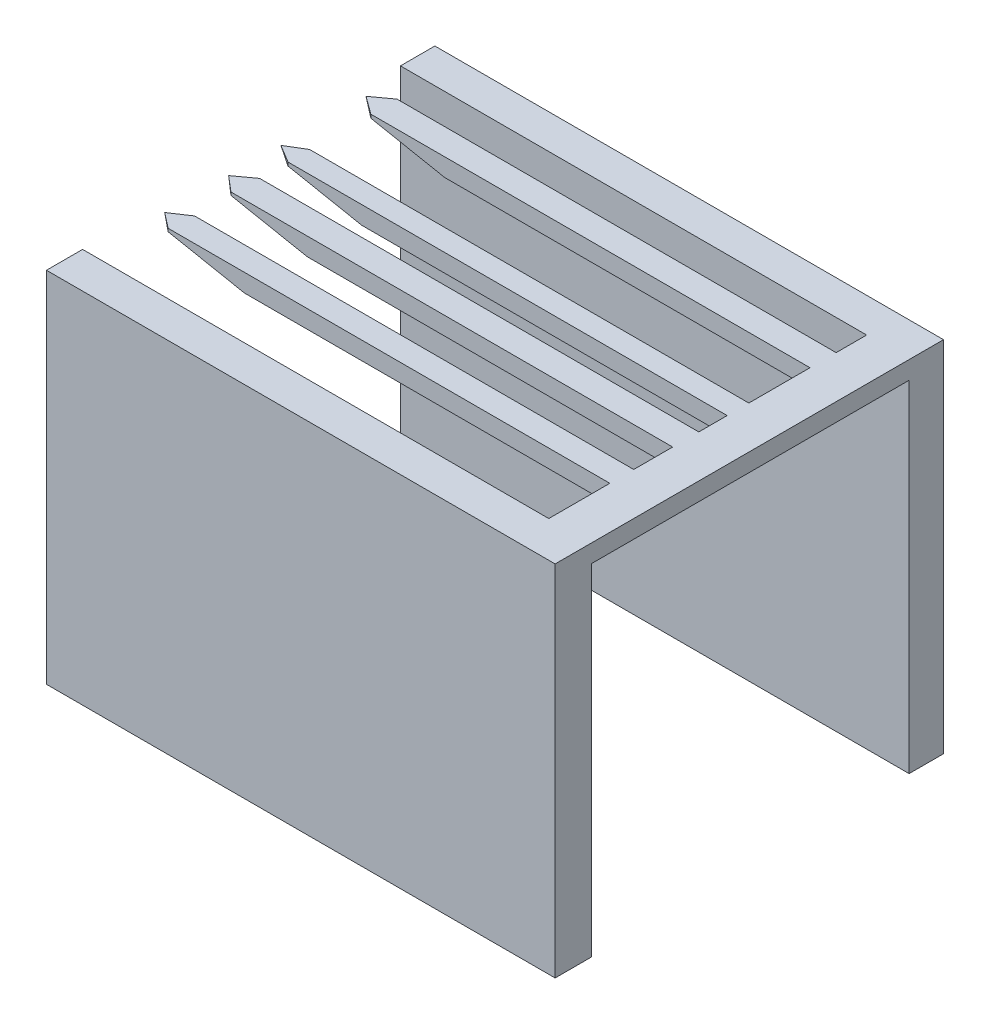
SolidWorks part; units mm, degrees
ref_plane "Front Plane" through (0, 0, 0) normal (0, 0, 1) x (1, 0, 0)
ref_plane "Top Plane" through (0, 0, 0) normal (0, 1, 0) x (1, 0, 0)
ref_plane "Right Plane" through (0, 0, 0) normal (1, 0, 0) x (0, 0, -1)
sketch "Sketch1" plane through (0, 0, 22.0657) normal (0, 1, 0) x (1, 0, 0)
  line L1 (-54.1532, 26.5268) -> (87.6897, 26.5268)
  line L2 (-54.1532, 26.5268) -> (-54.1532, -81.7796)
  line L3 (-54.1532, -81.7796) -> (87.6897, -81.7796)
  line L4 (87.6897, 26.5268) -> (87.6897, -81.7796)
  point P4 (87.6897, -81.7796)
extrude "Boss-Extrude1" add sketch "Sketch1" along normal blind 5
sketch "Sketch2" plane through (0, 5, 22.0657) normal (0, 1, 0) x (1, 0, 0)
  line L0 (87.6897, -81.7796) -> (87.6897, 26.5268) construction
  line L1 (-54.1532, -81.7796) -> (87.6897, -81.7796)
  line L2 (-54.1532, -81.7796) -> (-54.1532, -44.8027)
  line L3 (-54.1532, -44.8027) -> (57.7742, -44.8027)
  line L4 (87.6897, -81.7796) -> (87.6897, -44.8027)
  line L5 (57.7742, -44.8027) -> (57.7742, 16.927)
  line L6 (87.6897, 26.5268) -> (-54.1532, 26.5268) construction
  line L7 (57.7742, 26.5268) -> (87.6897, 26.5268)
  line L8 (87.6897, 26.5268) -> (87.6897, -44.8027)
  line L9 (-54.1532, 26.5268) -> (57.7742, 26.5268)
  line L10 (57.7742, 16.927) -> (-54.1532, 16.927)
  line L11 (-54.1532, 26.5268) -> (-54.1532, -81.7796) construction
  line L12 (-54.1532, 16.927) -> (-54.1532, 26.5268)
extrude "Boss-Extrude2" add sketch "Sketch2" along normal blind 95
sketch "Sketch3" plane through (0, 5, 22.0657) normal (0, 1, 0) x (1, 0, 0)
  line L4 (-54.1532, -44.8027) -> (57.7742, -44.8027)
  line L5 (57.7742, -44.8027) -> (57.7742, 16.927)
  line L6 (57.7742, 16.927) -> (-54.1532, 16.927)
  line L7 (-54.1532, 16.927) -> (-54.1532, -44.8027)
  line L8 (-54.1532, -44.8027) -> (57.7742, -44.8027)
  line L9 (57.7742, -44.8027) -> (57.7742, 16.927)
  line L10 (57.7742, 16.927) -> (-54.1532, 16.927)
  line L11 (-54.1532, 16.927) -> (-54.1532, -44.8027)
  dimension "D1" = 0
extrude "Cut-Extrude1" cut sketch "Sketch3" against normal blind 95
sketch "Sketch4" plane through (57.7742, 0, 22.0657) normal (-1, 0, 0) x (0, 0, 1)
  line L4 (-16.927, 100) -> (-16.927, 0)
  line L5 (-16.927, 0) -> (44.8027, 0)
  line L6 (44.8027, 0) -> (44.8027, 100)
  line L7 (44.8027, 100) -> (-16.927, 100)
  line L8 (-16.927, 100) -> (-16.927, 0)
  line L9 (-16.927, 0) -> (44.8027, 0)
  line L10 (44.8027, 0) -> (44.8027, 100)
  line L11 (44.8027, 100) -> (-16.927, 100)
  dimension "D1" = 0
extrude "Cut-Extrude2" cut sketch "Sketch4" against normal blind 95
sketch "Sketch5" plane through (0, 100, 0) normal (0, 1, 0) x (1, 0, 0)
  line L0 (-54.1532, -66.8683) -> (-54.1532, -103.8453) construction
  line L1 (-54.1532, -66.8683) -> (87.6897, -66.8683)
  line L2 (-54.1532, -66.8683) -> (-54.1532, -93.7696)
  line L3 (-54.1532, -93.7696) -> (87.6897, -93.7696)
  line L4 (87.6897, -66.8683) -> (87.6897, -93.7696)
  line L5 (87.6897, -66.8683) -> (-54.1532, -66.8683) construction
  line L6 (87.6897, -103.8453) -> (87.6897, -66.8683) construction
extrude "Cut-Extrude3" cut sketch "Sketch5" against normal blind 135
sketch "Sketch6" plane through (0, 100, 0) normal (0, 1, 0) x (1, 0, 0)
  line L5 (-54.1532, -103.8453) -> (87.6897, -103.8453) construction
  line L21 (87.6897, 4.4612) -> (75.8457, 4.4612)
  line L24 (87.6897, 4.4612) -> (87.6897, -103.8453)
  line L25 (87.6897, -103.8453) -> (75.8457, -103.8453)
  line L26 (75.8457, 4.4612) -> (75.8457, -13.6408)
  line L27 (75.8457, -20.9286) -> (75.8457, -37.9851)
  line L28 (-46.6105, -13.6408) -> (75.8457, -13.6408)
  line L30 (-46.6105, -20.9286) -> (75.8457, -20.9286)
  line L32 (-46.6105, -37.9851) -> (75.8457, -37.9851)
  line L34 (-46.6105, -44.0324) -> (75.8457, -44.0324)
  line L36 (-46.6105, -51.9404) -> (75.8457, -51.9404)
  line L38 (-47.3198, -59.2282) -> (75.8457, -59.2282)
  line L40 (-46.6105, -70.0823) -> (75.8457, -70.0823)
  line L42 (-47.3198, -76.7499) -> (75.8457, -76.7499)
  line L44 (75.8457, -44.0324) -> (75.8457, -51.9404)
  line L45 (75.8457, -59.2282) -> (75.8457, -70.0823)
  line L46 (75.8457, -76.7499) -> (75.8457, -103.8453)
  line L47 (-47.3198, -76.7499) -> (-51.6128, -73.4161)
  line L48 (-51.6128, -73.4161) -> (-46.6105, -70.0823)
  line L49 (-47.3198, -59.2282) -> (-51.6128, -55.5843)
  line L50 (-51.6128, -55.5843) -> (-46.6105, -51.9404)
  line L51 (-46.6105, -44.0324) -> (-51.6128, -41.0088)
  line L52 (-51.6128, -41.0088) -> (-46.6105, -37.9851)
  line L53 (-46.6105, -20.9286) -> (-51.6128, -17.2847)
  line L54 (-51.6128, -17.2847) -> (-46.6105, -13.6408)
extrude "Boss-Extrude3" add sketch "Sketch6" against normal blind 5
sketch "Sketch7" plane through (0, 0, 20.9286) normal (0, 0, 1) x (1, 0, 0)
  line L0 (-51.6128, 100) -> (-26.0346, 95)
  line L1 (-47.3198, 95) -> (75.8457, 95) construction
  line L2 (-26.0346, 95) -> (-51.6128, 95)
  line L3 (-51.6128, 95) -> (-51.6128, 100) construction
  line L4 (-47.3198, 95) -> (-51.6128, 95) construction
  line L5 (-51.6128, 95) -> (-51.6128, 100)
extrude "Cut-Extrude4" cut sketch "Sketch7" against normal blind 15 and the other way blind 65
